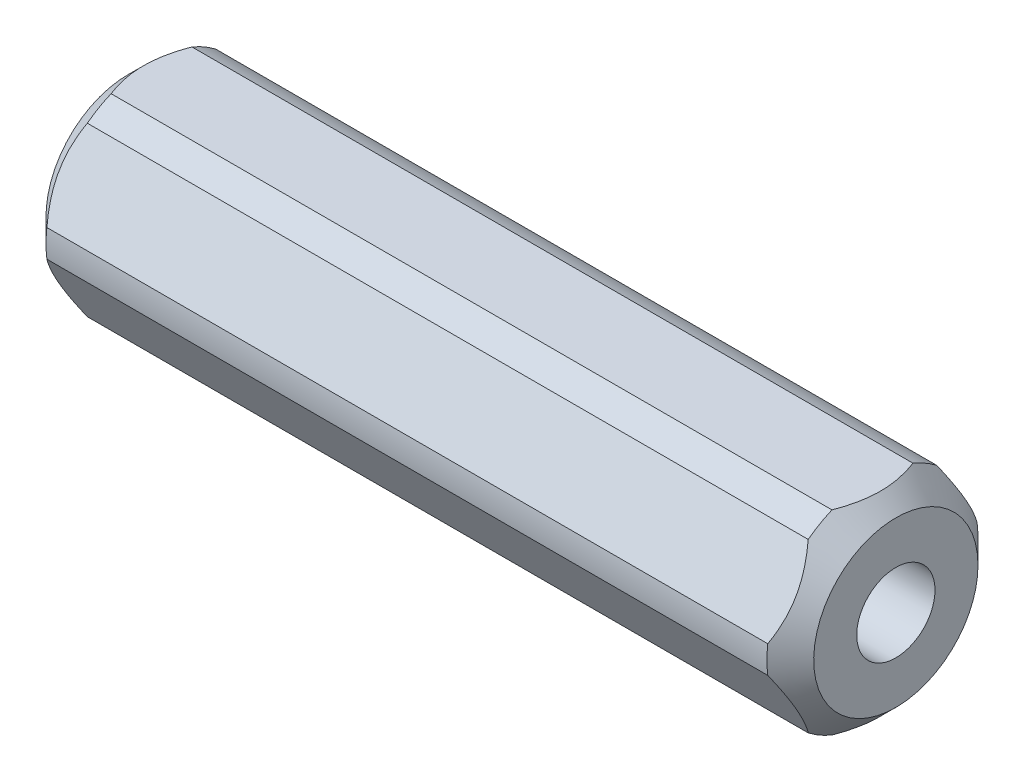
SolidWorks part; units mm, degrees
material "7075-O (SS)"
ref_plane "前视基准面" through (0, 0, 0) normal (0, 0, 1) x (1, 0, 0)
ref_plane "上视基准面" through (0, 0, 0) normal (0, 1, 0) x (1, 0, 0)
ref_plane "右视基准面" through (0, 0, 0) normal (1, 0, 0) x (0, 0, -1)
sketch "草图1" plane through (0, 0, 0) normal (1, 0, 0) x (0, 0, -1)
  line L1 (7.3323, 0) -> (3.6662, 6.35)
  line L2 (3.6662, 6.35) -> (-3.6662, 6.35)
  line L3 (-3.6662, 6.35) -> (-7.3323, 0)
  line L4 (-7.3323, 0) -> (-3.6662, -6.35)
  line L5 (-3.6662, -6.35) -> (3.6662, -6.35)
  line L6 (3.6662, -6.35) -> (7.3323, 0)
  circle A1 centre (0, 0) radius 6.35 construction
  dimension "D1" = 12.7
extrude "初始整轴" add sketch "草图1" along normal mid plane 50
sketch "草图8" plane through (0, 0, 0) normal (1, 0, 0) x (0, 0, -1)
  circle A0 centre (0, 0) radius 6.875
  circle A1 centre (0, 0) radius 8.875
  dimension "D1" = 13.75
  dimension "D2" = 2
extrude "整轴外圆" cut sketch "草图8" against normal through all both and the other way through all
sketch "草图9" plane through (0, 0, 0) normal (1, 0, 0) x (0, 0, -1)
  circle A0 centre (0, 0) radius 2.55
  dimension "D1" = 5.1
extrude "中心孔切除" cut sketch "草图9" against normal through all both and the other way through all
sketch "草图10" plane through (0, 0, 0) normal (0, 0, 1) x (1, 0, 0)
  line L0 (25, 0) -> (-25, 0) construction
  line L7 (0, 0) -> (0, 5.457) construction
  line L8 (-25, 5.457) -> (25, 5.457) construction
  line L12 (-26, 7.35) -> (-23, 7.35)
  line L13 (-26, 7.35) -> (-26, 4.35)
  line L14 (-23, 7.35) -> (-26, 4.35)
  line L15 (-25, 5.457) -> (-25, 0.893) construction
  line L16 (25, 6.35) -> (-25, 6.35) construction
  line L17 (23, 7.35) -> (26, 4.35)
  line L18 (26, 7.35) -> (26, 4.35)
  line L19 (26, 7.35) -> (23, 7.35)
  line L20 (-25, 0.893) -> (-25, -0.893) construction
  point P6 (0, 0)
  point P8 (0, 0)
  dimension "D1" = 3
  dimension "D2" = 3
  dimension "D3" = 1
  dimension "D4" = 1
revolve "初始倒角" cut sketch "草图10" angle 360 about L0
sketch "草图2" [suppressed] plane through (25, 0, 0) normal (1, 0, 0) x (0, 0, -1)
  circle A0 centre (0, 0) radius 4
  circle A1 centre (0, 0) radius 7.5
  dimension "D1" = 15
  dimension "右侧凸台直径" = 8
extrude "右侧凸台切除" [suppressed] cut sketch "草图2" against normal blind 5
chamfer "右侧凸台倒角" [suppressed] distance 0.3 angle 45
sketch "草图3" [suppressed] plane through (-25, 0, 0) normal (-1, 0, 0) x (0, 0, 1)
  circle A0 centre (0, 0) radius 4
  circle A1 centre (0, 0) radius 7.5
  dimension "D1" = 15
  dimension "左侧凸台直径" = 8
extrude "左侧凸台切除" [suppressed] cut sketch "草图3" against normal blind 5
chamfer "左侧凸台倒角" [suppressed] distance 0.3 angle 45
sketch "草图4" plane through (0, 0, 0) normal (0, 0, 1) x (1, 0, 0)
  line L0 (-13.3489, 0) -> (13.3489, 0) construction
  line L3 (14.5, 6.88) -> (15.5, 6.88)
  line L4 (14.5, 6.88) -> (14.5, 6)
  line L5 (14.5, 6) -> (15.5, 6)
  line L6 (15.5, 6.88) -> (15.5, 6)
  line L7 (15, 6.88) -> (15, -2.1923) construction
  point P6 (0, 0)
  dimension "D1" = 6
  dimension "D2" = 6.88
  dimension "槽1宽度" = 1
  dimension "槽1中心距离" = 15
revolve "卡簧槽1" [suppressed] cut sketch "草图4" angle 360 about L0
sketch "草图5" plane through (0, 0, 0) normal (0, 0, 1) x (1, 0, 0)
  line L0 (-10.9541, 0) -> (10.9541, 0) construction
  line L3 (-15.5, 6.88) -> (-14.5, 6.88)
  line L4 (-15.5, 6.88) -> (-15.5, 6)
  line L5 (-15.5, 6) -> (-14.5, 6)
  line L6 (-14.5, 6.88) -> (-14.5, 6)
  line L7 (-15, 6.88) -> (-15, -2.3192) construction
  point P6 (0, 0)
  dimension "D1" = 6
  dimension "D2" = 6.88
  dimension "槽2宽度" = 1
  dimension "槽2中心距离" = 15
revolve "卡簧槽2" [suppressed] cut sketch "草图5" angle 360 about L0
sketch "草图6" [suppressed] plane through (25, 0, 0) normal (1, 0, 0) x (0, 0, -1)
  circle A0 centre (0, 0) radius 3
  dimension "右侧攻丝直径" = 6
extrude "右侧攻丝切除" [suppressed] cut sketch "草图6" against normal blind 5
chamfer "右侧攻丝倒角" [suppressed] distance 0.5 angle 45
sketch "草图7" [suppressed] plane through (-25, 0, 0) normal (-1, 0, 0) x (0, 0, 1)
  circle A0 centre (0, 0) radius 3
  dimension "左侧攻丝直径" = 6
extrude "左侧攻丝切除" [suppressed] cut sketch "草图7" against normal blind 5
chamfer "左侧攻丝倒角" [suppressed] distance 0.5 angle 45
